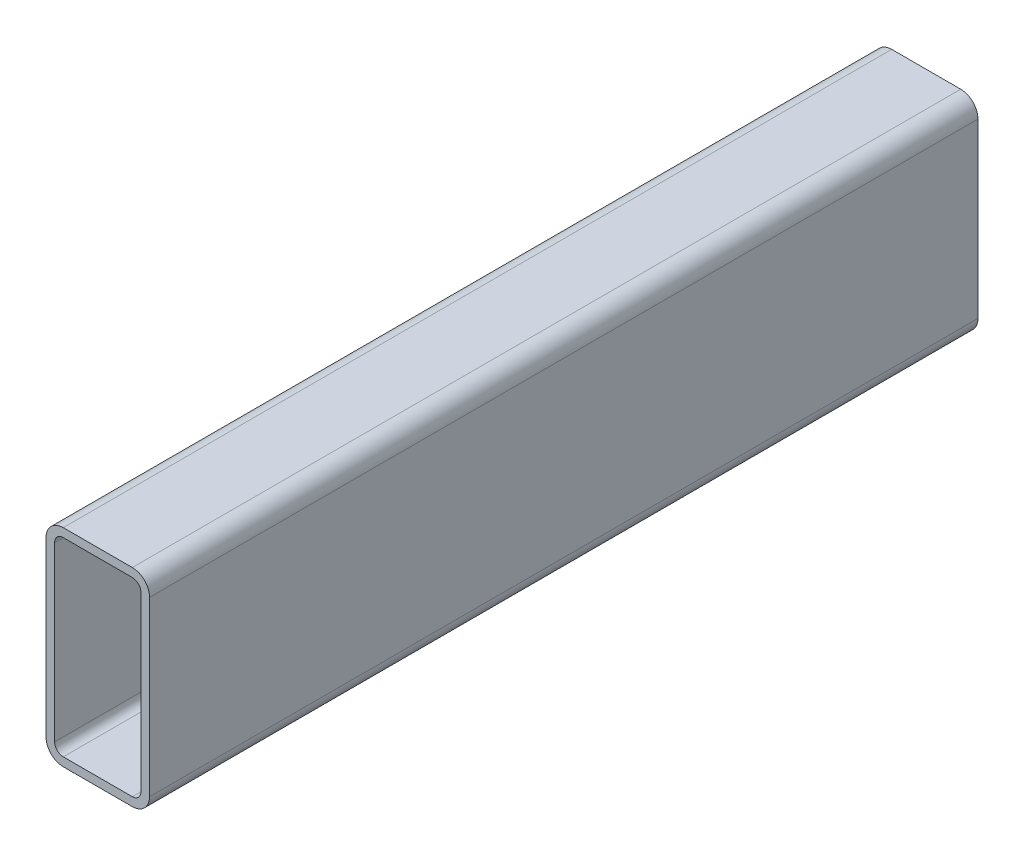
SolidWorks part; units mm, degrees
material "AISI 1020 Steel, Cold Rolled"
ref_plane "Front Plane" through (0, 0, 0) normal (0, 0, 1) x (1, 0, 0)
ref_plane "Top Plane" through (0, 0, 0) normal (0, 1, 0) x (1, 0, 0)
ref_plane "Right Plane" through (0, 0, 0) normal (1, 0, 0) x (0, 0, -1)
sketch "Sketch1" plane through (0, 0, 0) normal (0, 0, 1) x (1, 0, 0)
  line L0 (31.75, 0) -> (38.1, 0) construction
  line L1 (-25.4, -76.2) -> (25.4, -76.2)
  line L2 (-38.1, -63.5) -> (-38.1, 63.5)
  line L3 (-25.4, 76.2) -> (25.4, 76.2)
  line L4 (38.1, -63.5) -> (38.1, 63.5)
  line L5 (-38.1, -76.2) -> (38.1, 76.2) construction
  line L6 (-38.1, 76.2) -> (38.1, -76.2) construction
  line L7 (-25.4, -69.85) -> (25.4, -69.85)
  line L8 (-31.75, -63.5) -> (-31.75, 63.5)
  line L9 (-25.4, 69.85) -> (25.4, 69.85)
  line L10 (31.75, -63.5) -> (31.75, 63.5)
  line L11 (-31.75, -69.85) -> (31.75, 69.85) construction
  line L12 (-31.75, 69.85) -> (31.75, -69.85) construction
  line L14 (0, 69.85) -> (0, 76.2) construction
  arc A0 (-38.1, -63.5) -> (-25.4, -76.2) centre (-25.4, -63.5) ccw
  arc A1 (25.4, -76.2) -> (38.1, -63.5) centre (25.4, -63.5) ccw
  arc A2 (38.1, 63.5) -> (25.4, 76.2) centre (25.4, 63.5) ccw
  arc A3 (-38.1, 63.5) -> (-25.4, 76.2) centre (-25.4, 63.5) cw
  arc A4 (-25.4, -69.85) -> (-31.75, -63.5) centre (-25.4, -63.5) cw
  arc A5 (25.4, -69.85) -> (31.75, -63.5) centre (25.4, -63.5) ccw
  arc A6 (25.4, 69.85) -> (31.75, 63.5) centre (25.4, 63.5) cw
  arc A7 (-31.75, 63.5) -> (-25.4, 69.85) centre (-25.4, 63.5) cw
  point P0 (0, 0)
  point P6 (0, 0)
  dimension "D4" = 12.7
  dimension "D5" = 6.35
  dimension "D1" = 6.35
  dimension "D2" = 152.4
  dimension "D3" = 76.2
extrude "Boss-Extrude1" add sketch "Sketch1" along normal blind 609.6
equation "\"D5@Sketch1\"=\"Radius\"-\"Thichness\""
equation "\"D3@Sketch1\"=\"Width\""
equation "\"D2@Sketch1\"=\"Height\""
equation "\"D1@Sketch1\"=\"Thichness\""
equation "\"D4@Sketch1\"=\"Radius\""
equation "\"D1@Boss-Extrude1\"=\"Length\""
